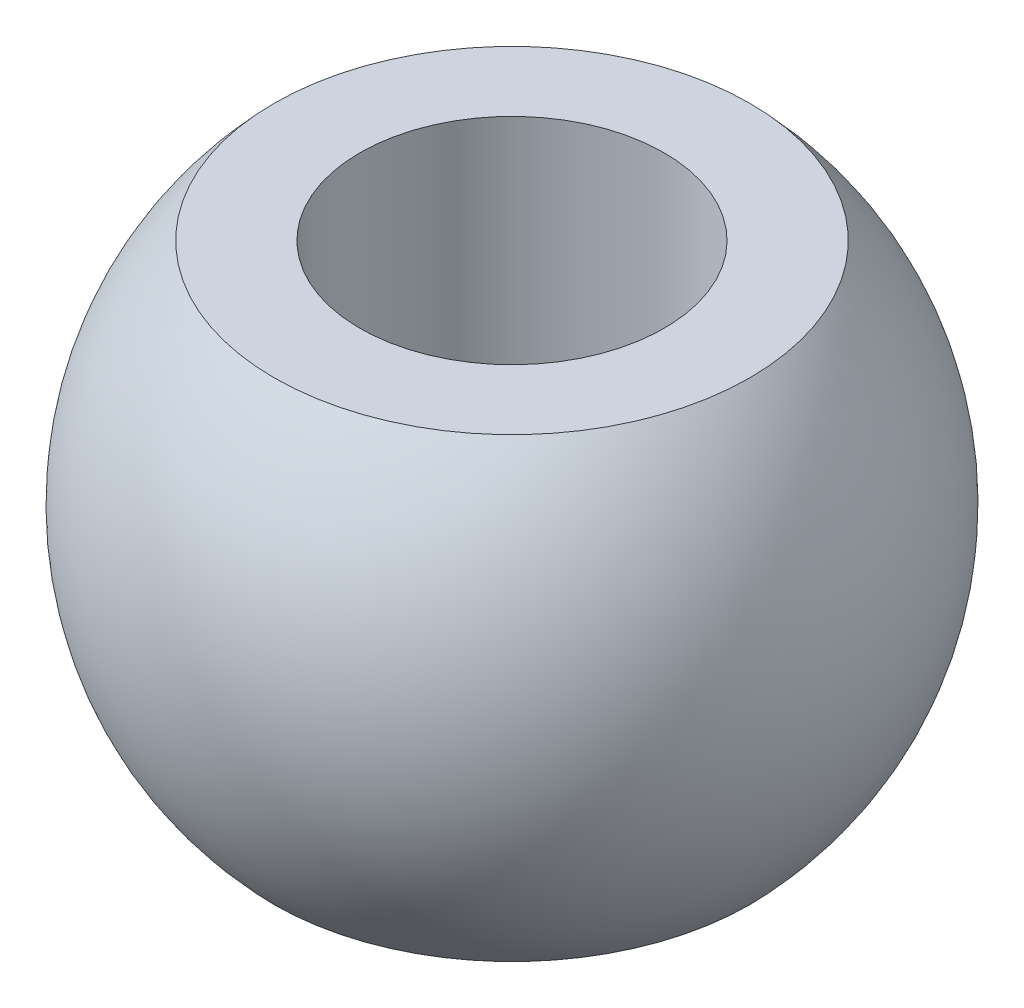
SolidWorks part; units mm, degrees
ref_plane "前视基准面" through (0, 0, 0) normal (0, 0, 1) x (1, 0, 0)
ref_plane "上视基准面" through (0, 0, 0) normal (0, 1, 0) x (1, 0, 0)
ref_plane "右视基准面" through (0, 0, 0) normal (1, 0, 0) x (0, 0, -1)
sketch "草图1" plane through (0, 0, 0) normal (0, 0, 1) x (1, 0, 0)
  line L0 (0, 7.8493) -> (0, -7.766) construction
  line L1 (0, 4.5) -> (4.6904, 4.5)
  line L2 (-8.4205, 0) -> (8.4954, 0) construction
  line L3 (0, -4.5) -> (4.6904, -4.5)
  line L4 (0, 4.5) -> (0, -4.5)
  arc A0 (-4.5, 4.6904) -> (-4.5, -4.6904) centre (0, 0) ccw construction
  arc A1 (4.6904, -4.5) -> (4.6904, 4.5) centre (0, 0) ccw
  dimension "D1" = 13
  dimension "D2" = 9
revolve "旋转2" add sketch "草图1" angle 360 about L4
sketch "草图2" plane through (0, 4.5, 0) normal (0, 1, 0) x (1, 0, 0)
  circle A0 centre (0, 0) radius 3
  dimension "D1" = 6
extrude "切除-拉伸1" cut sketch "草图2" against normal through all
